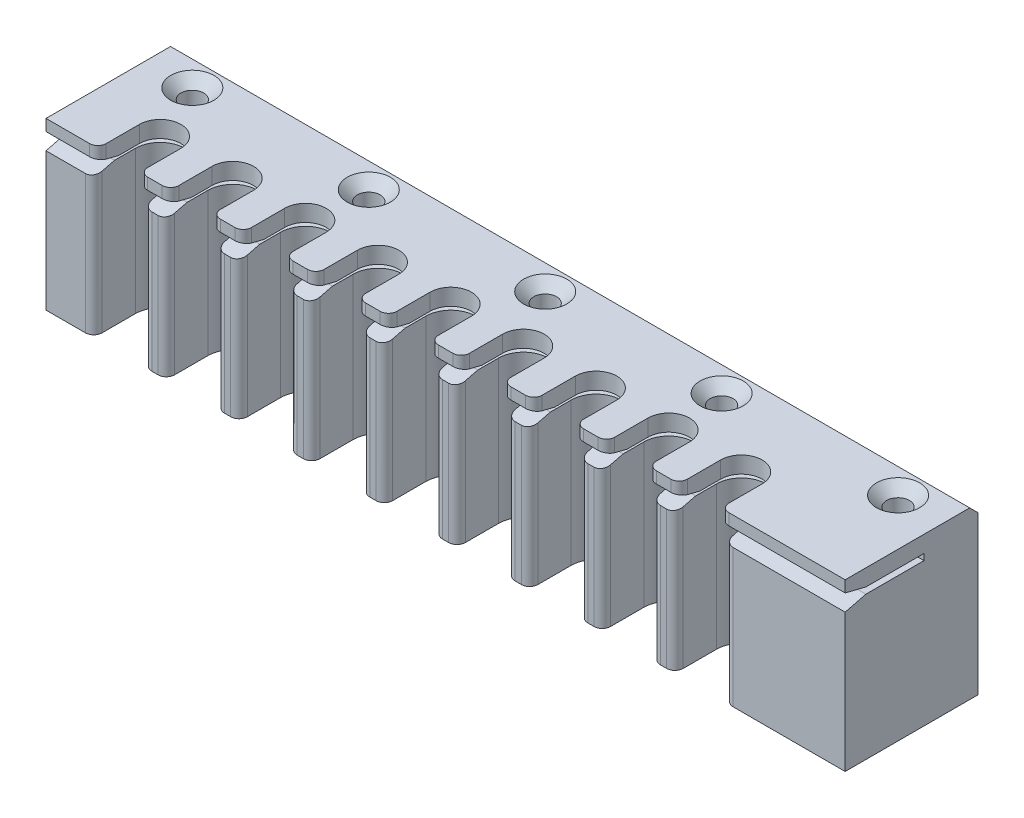
SolidWorks part; units mm, degrees
material "3.1355 (EN-AW 2024)"
ref_plane "Front" through (0, 0, 0) normal (0, 0, 1) x (1, 0, 0)
ref_plane "Top" through (0, 0, 0) normal (0, 1, 0) x (1, 0, 0)
ref_plane "Right" through (0, 0, 0) normal (1, 0, 0) x (0, 0, -1)
sketch "Эскиз1" plane through (0, 0, 0) normal (0, 1, 0) x (1, 0, 0)
  line L1 (-96.25, 16) -> (96.25, 16)
  line L2 (-96.25, 16) -> (-96.25, -16)
  line L3 (-96.25, -16) -> (96.25, -16)
  line L4 (96.25, 16) -> (96.25, -16)
  line L5 (-96.25, 16) -> (96.25, -16) construction
  line L6 (-96.25, -16) -> (96.25, 16) construction
  point P0 (0, 0)
  dimension "D1" = 32
  dimension "D2" = 192.5
extrude "База" add sketch "Эскиз1" along normal blind 34.5
sketch "Эскиз4" plane through (0, 34.5, 0) normal (0, 1, 0) x (1, 0, 0)
  line L0 (96.25, -16) -> (96.25, 16) construction
  line L1 (-96.25, 16) -> (96.25, 16)
  line L2 (-96.25, 16) -> (-96.25, 3)
  line L3 (-96.25, 3) -> (96.25, 3)
  line L4 (96.25, 16) -> (96.25, 3)
  dimension "D2" = 13
extrude "Вынос для верха" add sketch "Эскиз4" along normal blind 1.5
sketch "Эскиз2" plane through (0, 34.5, 0) normal (0, 1, 0) x (1, 0, 0)
  line L0 (-84.75, -16) -> (-84.75, -6)
  line L1 (-96.25, -16) -> (96.25, -16) construction
  line L2 (-72.75, -16) -> (-72.75, -6)
  line L3 (-84.75, -16) -> (-72.75, -16)
  line L5 (-96.25, 3) -> (-96.25, -16) construction
  arc A0 (-84.75, -6) -> (-72.75, -6) centre (-78.75, -6) cw
  dimension "D1" = 12
  dimension "D2" = 10
  dimension "D3" = 17.5
extrude "СоплоНиз" cut sketch "Эскиз2" against normal through all
sketch "Эскиз5" plane through (0, 36, 0) normal (0, 1, 0) x (1, 0, 0)
  line L1 (-96.25, 16) -> (96.25, 16)
  line L2 (-96.25, 16) -> (-96.25, -16)
  line L3 (-96.25, -16) -> (96.25, -16)
  line L4 (96.25, 16) -> (96.25, -16)
extrude "Верх" add sketch "Эскиз5" along normal blind 4
sketch "Эскиз3" plane through (-96.25, 0, 0) normal (-1, 0, 0) x (0, 0, 1)
  line L5 (16, 33.25) -> (11, 34.5)
  line L6 (16, 34.5) -> (16, 0) construction
  line L7 (-3, 34.5) -> (16, 34.5) construction
  line L8 (11, 34.5) -> (11, 36)
  line L9 (-3, 36) -> (16, 36) construction
  line L10 (11, 36) -> (16, 37.25)
  line L11 (16, 40) -> (16, 36) construction
  line L12 (16, 37.25) -> (16, 33.25)
  point P13 (11, 35.25)
  dimension "D1" = 1.25
  dimension "D2" = 1.25
  dimension "D3" = 5
extrude "ВырезНаправляющих" cut sketch "Эскиз3" against normal through all
sketch "Эскиз7" plane through (0, 40, 0) normal (0, 1, 0) x (1, 0, 0)
  line L0 (-83.75, -6) -> (-83.75, -16)
  line L1 (-96.25, -16) -> (96.25, -16) construction
  line L2 (-73.75, -6) -> (-73.75, -16)
  line L3 (-73.75, -16) -> (-83.75, -16)
  arc A0 (-73.75, -6) -> (-83.75, -6) centre (-78.75, -6) ccw
  dimension "D1" = 10
extrude "СоплоВерх" cut sketch "Эскиз7" against normal up to next and the other way through all
fillet "Скругление1" radius 2 4 edges at (-84.75, 16.625, 16) (-72.75, 16.625, 16) (-73.75, 38.625, 16) (-83.75, 38.625, 16)
pattern_linear "Линейный массив1" count 9 spacing 17.5 along (1, 0, 0) of "СоплоНиз", "СоплоВерх", "Скругление1"
hole_wizard "Крепление - M5" positions "Эскиз8" profile "Эскиз9" countersink size "M5" standard "DIN" end condition through all
sketch "Эскиз8" plane through (0, 40, 0) normal (0, 1, 0) x (1, 0, 0)
  line L4 (96.25, 16) -> (-96.25, 16) construction
  line L5 (-85, 8) -> (-42.5, 8) construction
  line L6 (-42.5, 8) -> (0, 8) construction
  line L7 (0, 8) -> (42.5, 8) construction
  line L8 (42.5, 8) -> (85, 8) construction
  point P0 (-85, 8)
  point P2 (0, 8)
  point P4 (85, 8)
  point P16 (42.5, 8)
  point P18 (-42.5, 8)
  dimension "D1" = 170
  dimension "D2" = 8
sketch "Эскиз9" plane through (-85, 40, -8) normal (1, 0, 0) x (0, 0, 1)
  line L0 (0, 0) -> (0, 40)
  line L1 (0, 40) -> (2.75, 40)
  line L2 (2.75, 40) -> (2.75, 2.45)
  line L3 (2.75, 2.45) -> (5.2, 0)
  line L5 (5.2, 0) -> (0, 0)
  line L6 (-2.75, 2.45) -> (-5.2, 0) construction
  line L11 (0, -6.35) -> (0, 107.95) construction
  dimension "Диаметр сквозного отверстия" = 5.5
  dimension "Глубина сквозного отверстия" = 40
  dimension "Диаметр передней зенковки" = 10.4
  dimension "Угол передней зенковки" = 90
chamfer "Фаска1" distance 2 angle 45 1 edges at (0, 40, -16)
